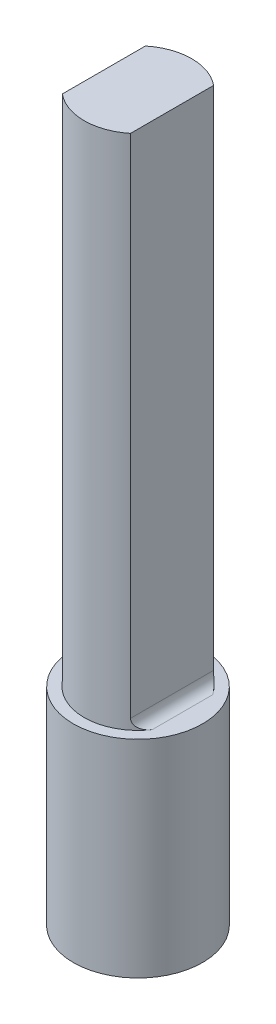
SolidWorks part; units mm, degrees
ref_plane "Front" through (0, 0, 0) normal (0, 0, 1) x (1, 0, 0)
ref_plane "Top" through (0, 0, 0) normal (0, 1, 0) x (1, 0, 0)
ref_plane "Right" through (0, 0, 0) normal (1, 0, 0) x (0, 0, -1)
sketch "Sketch1" plane through (0, 0, 0) normal (0, 1, 0) x (1, 0, 0)
  circle A0 centre (0, 0) radius 3.125
  dimension "D1" = 6.25
extrude "Boss-Extrude1" add sketch "Sketch1" along normal mid plane 10
sketch "Sketch2" plane through (0, 5, 0) normal (0, 1, 0) x (1, 0, 0)
  line L0 (-1.65, -2.0094) -> (-1.65, 2.0094)
  line L1 (1.65, 2.0094) -> (1.65, -2.0094)
  line L2 (-1.65, 0) -> (1.65, 0) construction
  arc A0 (-1.65, -2.0094) -> (1.65, -2.0094) centre (0, 0) ccw
  arc A1 (1.65, 2.0094) -> (-1.65, 2.0094) centre (0, 0) ccw
  point P9 (1.9848, 0)
  point P10 (0, 0)
  dimension "D1" = 5.2
  dimension "D2" = 3.3
extrude "Boss-Extrude2" add sketch "Sketch2" along normal blind 25
fillet "Fillet1" radius 0.5 2 edges at (1.65, 5, 0) (-1.65, 5, 0)
